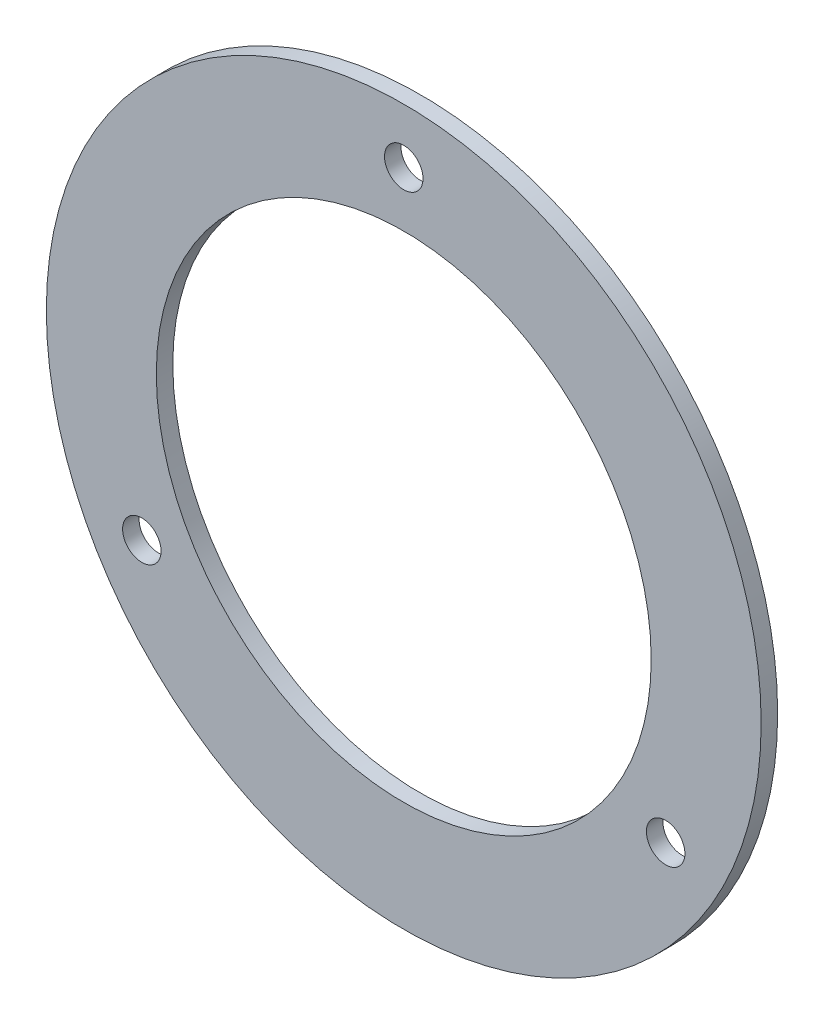
SolidWorks part; units mm, degrees
material "PE High Density Film"
ref_plane "Front Plane" through (0, 0, 0) normal (0, 0, 1) x (1, 0, 0)
ref_plane "Top Plane" through (0, 0, 0) normal (0, 1, 0) x (1, 0, 0)
ref_plane "Right Plane" through (0, 0, 0) normal (1, 0, 0) x (0, 0, -1)
sketch "Sketch1" plane through (0, 0, 0) normal (0, 0, 1) x (1, 0, 0)
  circle A0 centre (0, 0) radius 45
  circle A1 centre (0, 0) radius 65
  dimension "D1" = 90
  dimension "D2" = 130
extrude "Boss-Extrude1" add sketch "Sketch1" along normal blind 3
sketch "Sketch2" plane through (0, 0, 3) normal (0, 0, 1) x (1, 0, 0)
  circle A1 centre (0, 55) radius 3.5
  dimension "D1" = 55
  dimension "D2" = 7
extrude "Cut-Extrude1" cut sketch "Sketch2" against normal blind 3
pattern_circular "CirPattern1" count 3 over 360 about axis through (0, 0, 0) along (0, 0, 1) of "Cut-Extrude1"
